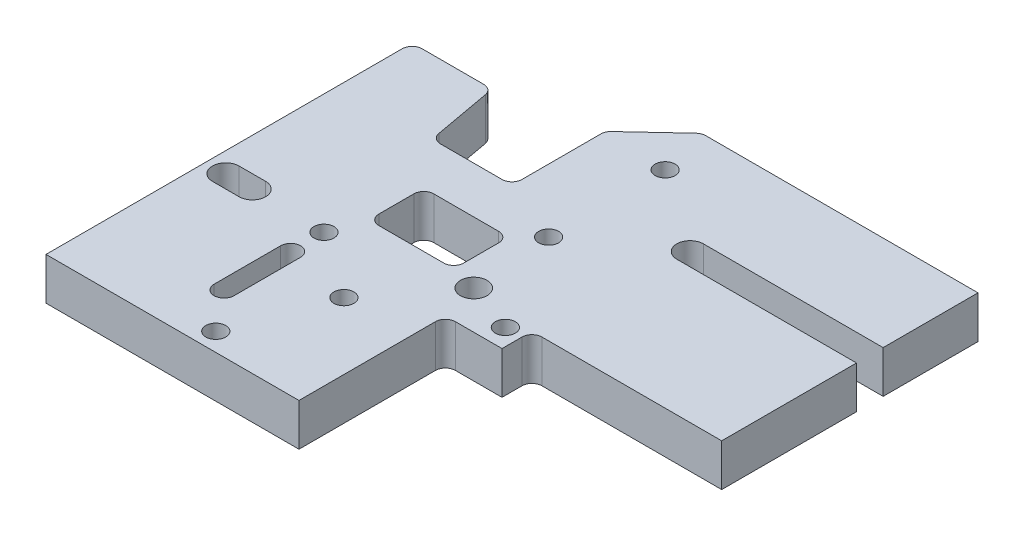
SolidWorks part; units mm, degrees
material "1060 Alloy"
ref_plane "Front Plane" through (0, 0, 0) normal (0, 0, 1) x (1, 0, 0)
ref_plane "Top Plane" through (0, 0, 0) normal (0, 1, 0) x (1, 0, 0)
ref_plane "Right Plane" through (0, 0, 0) normal (1, 0, 0) x (0, 0, -1)
sketch "Sketch1" plane through (0, 0, 0) normal (0, 1, 0) x (1, 0, 0)
  line L0 (48, 228) -> (48, 71.7384) construction
  line L2 (0, 20) -> (0, 104)
  line L4 (96, 20) -> (96, 104)
  line L5 (33.5, 114) -> (26, 107)
  line L6 (26, 107) -> (26, 93)
  line L7 (26, 93) -> (14, 93)
  line L8 (14, 93) -> (12, 104)
  line L9 (12, 104) -> (0, 104)
  line L10 (62.5, 114) -> (70, 107)
  line L11 (70, 107) -> (70, 93)
  line L12 (70, 93) -> (82, 93)
  line L13 (82, 93) -> (84, 104)
  line L14 (84, 104) -> (96, 104)
  line L15 (33.5, 114) -> (62.5, 114)
  line L16 (0, 20) -> (7, 9)
  line L17 (7, 9) -> (7, 0)
  line L18 (89, 9) -> (89, 0)
  line L19 (96, 20) -> (89, 9)
  line L20 (7, 0) -> (34, 0)
  line L21 (34, 0) -> (34, 8)
  line L22 (34, 8) -> (62, 8)
  line L23 (89, 0) -> (62, 0)
  line L24 (62, 0) -> (62, 8)
  line L25 (76.25, 21.75) -> (63.5, 21.75)
  line L26 (19.75, 30) -> (32.5, 30)
  line L27 (19.75, 30) -> (19.75, 21.75)
  line L28 (19.75, 21.75) -> (32.5, 21.75)
  line L29 (32.5, 30) -> (32.5, 21.75)
  line L30 (63.5, 30) -> (63.5, 21.75)
  line L31 (76.25, 30) -> (63.5, 30)
  line L32 (76.25, 30) -> (76.25, 21.75)
  line L33 (0, 53.875) -> (96, 53.875) construction
  line L34 (76.25, 77.75) -> (76.25, 86)
  line L35 (76.25, 77.75) -> (63.5, 77.75)
  line L36 (63.5, 77.75) -> (63.5, 86)
  line L37 (76.25, 86) -> (63.5, 86)
  line L38 (19.75, 86) -> (32.5, 86)
  line L39 (32.5, 77.75) -> (32.5, 86)
  line L40 (19.75, 77.75) -> (32.5, 77.75)
  line L41 (19.75, 77.75) -> (19.75, 86)
  line L42 (3, 75) -> (7, 75)
  line L43 (3, 71) -> (7, 71)
  line L44 (93, 75) -> (89, 75)
  line L45 (93, 71) -> (89, 71)
  line L46 (0, 54) -> (96, 54) construction
  line L47 (93, 37) -> (89, 37)
  line L48 (93, 33) -> (89, 33)
  line L49 (3, 33) -> (7, 33)
  line L50 (3, 37) -> (7, 37)
  line L51 (15, 48.5252) -> (23, 48.5252)
  line L52 (23, 45.5252) -> (15, 45.5252)
  line L53 (81, 48.5252) -> (73, 48.5252)
  line L54 (73, 45.5252) -> (81, 45.5252)
  line L55 (16.5, 67.75) -> (16.5, 57.75)
  line L56 (19.5, 67.75) -> (19.5, 57.75)
  line L57 (76.5, 67.75) -> (76.5, 57.75)
  line L58 (79.5, 67.75) -> (79.5, 57.75)
  line L59 (46.5, 29) -> (38, 29)
  line L60 (38, 29) -> (38, 71)
  line L61 (38, 71) -> (46.5, 71)
  line L62 (46.5, 29) -> (46.5, 26)
  line L63 (18.7278, 50) -> (57.2722, 50) construction
  line L64 (46.5, 71) -> (46.5, 74)
  line L65 (49.5, 29) -> (49.5, 26)
  line L66 (49.5, 29) -> (58, 29)
  line L67 (58, 29) -> (58, 71)
  line L68 (49.5, 71) -> (49.5, 74)
  line L69 (58, 71) -> (49.5, 71)
  line L70 (35.5, 106.5) -> (60.5, 89) construction
  circle A0 centre (12.5, 3) radius 1.5
  circle A1 centre (28, 3) radius 1.5
  circle A2 centre (68, 3) radius 1.5
  circle A3 centre (83.5, 3) radius 1.5
  circle A4 centre (14, 13) radius 3
  circle A5 centre (27, 13) radius 3
  circle A6 centre (69, 13) radius 3
  circle A7 centre (82, 13) radius 3
  arc A8 (3, 75) -> (3, 71) centre (3, 73) ccw
  arc A10 (7, 71) -> (7, 75) centre (7, 73) ccw
  arc A11 (89, 71) -> (89, 75) centre (89, 73) cw
  arc A12 (93, 75) -> (93, 71) centre (93, 73) cw
  arc A13 (93, 33) -> (93, 37) centre (93, 35) ccw
  arc A14 (89, 37) -> (89, 33) centre (89, 35) ccw
  arc A15 (7, 37) -> (7, 33) centre (7, 35) cw
  arc A16 (3, 33) -> (3, 37) centre (3, 35) cw
  circle A17 centre (22.75, 42.455) radius 1.5
  arc A18 (23, 45.5252) -> (23, 48.5252) centre (23, 47.0252) ccw
  arc A19 (15, 48.5252) -> (15, 45.5252) centre (15, 47.0252) ccw
  circle A20 centre (22.75, 51.7511) radius 1.5
  circle A21 centre (73.25, 42.455) radius 1.5
  arc A22 (73, 45.5252) -> (73, 48.5252) centre (73, 47.0252) cw
  arc A23 (81, 48.5252) -> (81, 45.5252) centre (81, 47.0252) cw
  circle A24 centre (73.25, 51.7511) radius 1.5
  circle A25 centre (18, 72.75) radius 1.5
  arc A26 (19.5, 67.75) -> (16.5, 67.75) centre (18, 67.75) ccw
  arc A27 (16.5, 57.75) -> (19.5, 57.75) centre (18, 57.75) ccw
  circle A28 centre (28, 65.75) radius 1.5
  circle A29 centre (68, 65.75) radius 1.5
  circle A30 centre (78, 72.75) radius 1.5
  arc A31 (79.5, 57.75) -> (76.5, 57.75) centre (78, 57.75) cw
  arc A32 (76.5, 67.75) -> (79.5, 67.75) centre (78, 67.75) cw
  circle A33 centre (36.5, 76.75) radius 2
  circle A34 centre (59.5, 76.75) radius 2
  circle A35 centre (35.5, 89) radius 1.5
  circle A36 centre (35.5, 106.5) radius 1.5
  circle A37 centre (60.5, 89) radius 1.5
  circle A38 centre (60.5, 106.5) radius 1.5
  arc A39 (46.5, 26) -> (49.5, 26) centre (48, 26) ccw
  arc A40 (46.5, 74) -> (49.5, 74) centre (48, 74) cw
  circle A41 centre (44, 26) radius 1.5
  circle A42 centre (52, 26) radius 1.5
  circle A43 centre (52, 74) radius 1.5
  circle A44 centre (44, 74) radius 1.5
  circle A45 centre (48, 97.75) radius 2
  point P8 (48, 149.8692)
  point P28 (48, 8)
  point P150 (38, 50)
  dimension "D13" = 3
  dimension "D14" = 3
  dimension "D15" = 5.5
  dimension "D16" = 6
  dimension "D17" = 3
  dimension "D18" = 6
  dimension "D19" = 13
  dimension "D20" = 14
  dimension "D21" = 13
  dimension "D27" = 4
  dimension "D28" = 4
  dimension "D29" = 4
  dimension "D30" = 31
  dimension "D32" = 3
  dimension "D34" = 3
  dimension "D35" = 3
  dimension "D36" = 22.75
  dimension "D37" = 3
  dimension "D39" = 15
  dimension "D40" = 3
  dimension "D41" = 11
  dimension "D42" = 5
  dimension "D43" = 5
  dimension "D44" = 10
  dimension "D45" = 3
  dimension "D46" = 10
  dimension "D47" = 7
  dimension "D48" = 4
  dimension "D49" = 4
  dimension "D50" = 1
  dimension "D51" = 3
  dimension "D52" = 3
  dimension "D53" = 3
  dimension "D54" = 17.5
  dimension "D55" = 21
  dimension "D60" = 3
  dimension "D61" = 3
  dimension "D58" = 3
  dimension "D62" = 4
  dimension "D63" = 4
  dimension "D1" = 10
  dimension "D2" = 96
  dimension "D3" = 12
  dimension "D4" = 21
  dimension "D5" = 7
  dimension "D6" = 7.5
  dimension "D7" = 12
  dimension "D8" = 2
  dimension "D9" = 27
  dimension "D10" = 7
  dimension "D11" = 9
  dimension "D12" = 8
  dimension "D22" = 8.25
  dimension "D23" = 12.75
  dimension "D24" = 21.75
  dimension "D25" = 19.75
  dimension "D26" = 23.875
  dimension "D31" = 114
  dimension "D33" = 17
  dimension "D38" = 8
  dimension "D56" = 42
  dimension "D57" = 38
  dimension "D59" = 1.5
extrude "Boss-Extrude1" add sketch "Sketch1" along normal blind 6.35
fillet "Fillet1" radius 1.5 42 edges at (38, 3.175, -29) (58, 3.175, -71) (63.5, 3.175, -30) (63.5, 3.175, -86) (32.5, 3.175, -86) (32.5, 3.175, -30) (76.25, 3.175, -30) (76.25, 3.175, -86) (19.75, 3.175, -77.75) (63.5, 3.175, -77.75) (63.5, 3.175, -21.75) (19.75, 3.175, -21.75) (32.5, 3.175, -21.75) (32.5, 3.175, -77.75) (76.25, 3.175, -77.75) (58, 3.175, -29) (76.25, 3.175, -21.75) (0, 3.175, -104) (12, 3.175, -104) (14, 3.175, -93) (26, 3.175, -93) (26, 3.175, -107) (33.5, 3.175, -114) (62.5, 3.175, -114) (70, 3.175, -107) (70, 3.175, -93) (82, 3.175, -93) (84, 3.175, -104) (96, 3.175, -104) (96, 3.175, -20) (89, 3.175, -9) (89, 3.175, 0) (62, 3.175, -8) (62, 3.175, 0) (19.75, 3.175, -86) (38, 3.175, -71) (19.75, 3.175, -30) (34, 3.175, -8) (34, 3.175, 0) (0, 3.175, -20) (7, 3.175, -9) (7, 3.175, 0)
ref_plane "Plane1" through (48, 0, 0) normal (1, 0, 0) x (0, 0, -1)
sketch "Sketch3" plane through (48, 0, 0) normal (1, 0, 0) x (0, 0, -1)
  line L1 (-6.4167, 7.5787) -> (123.2615, 7.5787)
  line L2 (-6.4167, 7.5787) -> (-6.4167, -5.6973)
  line L3 (-6.4167, -5.6973) -> (123.2615, -5.6973)
  line L4 (123.2615, 7.5787) -> (123.2615, -5.6973)
extrude "Cut-Extrude1" cut sketch "Sketch3" along normal blind 56
sketch "Sketch4" plane through (48, 0, 0) normal (1, 0, 0) x (0, 0, -1)
  line L4 (114, 0) -> (114, 6.35)
  line L5 (114, 6.35) -> (99.75, 6.35)
  line L6 (99.75, 6.35) -> (99.75, 0)
  line L7 (99.75, 0) -> (114, 0)
  line L8 (114, 0) -> (114, 6.35)
  line L9 (114, 6.35) -> (99.75, 6.35)
  line L10 (99.75, 6.35) -> (99.75, 0)
  line L11 (99.75, 0) -> (114, 0)
  line L12 (75.5, 0) -> (95.75, 0)
  line L13 (95.75, 0) -> (95.75, 6.35)
  line L14 (95.75, 6.35) -> (75.5, 6.35)
  line L15 (75.5, 6.35) -> (75.5, 0)
  line L16 (75.5, 0) -> (95.75, 0)
  line L17 (95.75, 0) -> (95.75, 6.35)
  line L18 (95.75, 6.35) -> (75.5, 6.35)
  line L19 (75.5, 6.35) -> (75.5, 0)
  line L28 (8, 6.35) -> (8, 0)
  line L29 (8, 0) -> (24.5, 0)
  line L30 (24.5, 0) -> (24.5, 6.35)
  line L31 (24.5, 6.35) -> (8, 6.35)
  line L32 (8, 6.35) -> (8, 0)
  line L33 (8, 0) -> (24.5, 0)
  line L34 (24.5, 0) -> (24.5, 6.35)
  line L35 (24.5, 6.35) -> (8, 6.35)
  dimension "D1" = 0
  dimension "D2" = 0
  dimension "D4" = 0
extrude "Boss-Extrude2" add sketch "Sketch4" along normal blind 25
mirror "Mirror1" about plane through (73, 0, 0) normal (1, 0, 0) of bodies 103
ref_plane "Plane2" through (75, 0, 0) normal (1, 0, 0) x (0, 0, -1)
sketch "Sketch5" plane through (75, 0, 0) normal (1, 0, 0) x (0, 0, -1)
  line L1 (-24.6869, 38.3801) -> (134.1511, 38.3801)
  line L2 (-24.6869, 38.3801) -> (-24.6869, -30.8448)
  line L3 (-24.6869, -30.8448) -> (134.1511, -30.8448)
  line L4 (134.1511, 38.3801) -> (134.1511, -30.8448)
extrude "Cut-Extrude2" cut sketch "Sketch5" along normal blind 86
sketch "Sketch6" plane through (38, 0, 0) normal (1, 0, 0) x (0, 0, -1)
  line L0 (48.9, 6.35) -> (48.9, 0)
  line L1 (30.5, 6.35) -> (30.5, 0) construction
  line L3 (49, 0) -> (49, 6.35)
  line L4 (69.5, 0) -> (30.5, 0) construction
  line L5 (69.5, 6.35) -> (30.5, 6.35) construction
  line L6 (48.9, 6.35) -> (49, 6.35)
  line L7 (48.9, 0) -> (49, 0)
  dimension "D1" = 18.4
  dimension "D2" = 0.1
extrude "Cut-Extrude3" cut sketch "Sketch6" against normal blind 49 and the other way blind 10
ref_plane "Plane3" through (0, 0, -48.91) normal (0, 0, -1) x (-1, 0, 0)
sketch "Sketch7" plane through (0, 0, -48.91) normal (0, 0, -1) x (-1, 0, 0)
  line L1 (-82.8539, 16.7318) -> (5.6106, 16.7318)
  line L2 (-82.8539, 16.7318) -> (-82.8539, -6.3838)
  line L3 (-82.8539, -6.3838) -> (5.6106, -6.3838)
  line L4 (5.6106, 16.7318) -> (5.6106, -6.3838)
extrude "Cut-Extrude4" cut sketch "Sketch7" against normal blind 68 contours L2 L3 L4 L1
